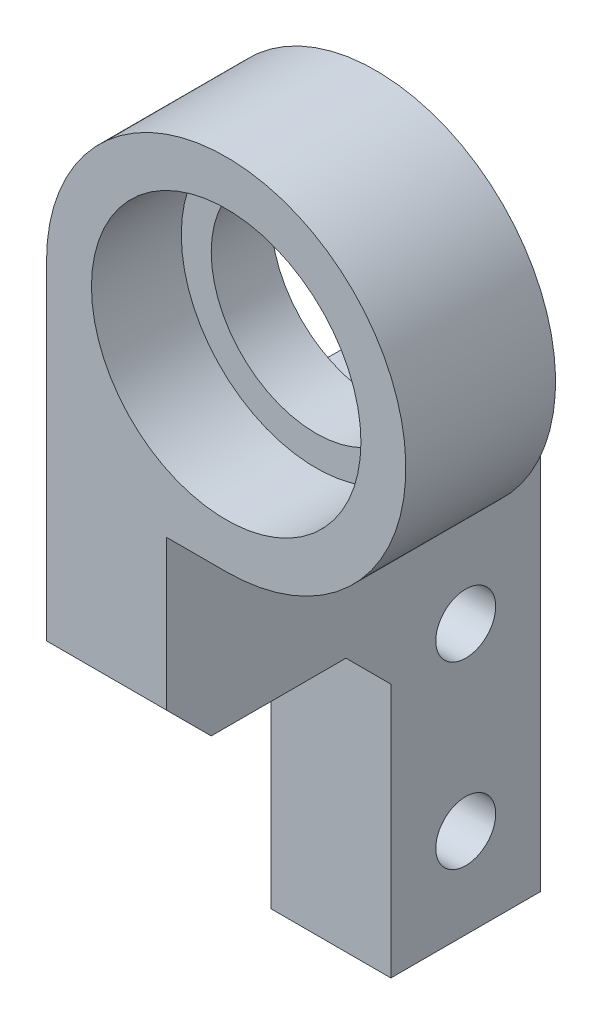
SolidWorks part; units mm, degrees
material "1060 合金"
ref_plane "前视基准面" through (0, 0, 0) normal (0, 0, 1) x (1, 0, 0)
ref_plane "上视基准面" through (0, 0, 0) normal (0, 1, 0) x (1, 0, 0)
ref_plane "右视基准面" through (0, 0, 0) normal (1, 0, 0) x (0, 0, -1)
sketch "草图1" plane through (0, 0, 0) normal (0, 0, 1) x (1, 0, 0)
  line L0 (0, 0) -> (8, 0)
  line L1 (8, 0) -> (8, 33)
  line L2 (0, 0) -> (0, 45)
  line L3 (12, 33) -> (8, 33)
  arc A0 (12, 33) -> (0, 45) centre (12, 45) ccw
  circle A1 centre (12, 45) radius 7
  dimension "D2" = 24
  dimension "D4" = 14
  dimension "D1" = 8
  dimension "D3" = 45
extrude "凸台-拉伸1" add sketch "草图1" along normal mid plane 25
sketch "草图5" plane through (0, 0, 0) normal (1, 0, 0) x (0, 0, -1)
  line L0 (-12.5, 57) -> (-12.5, 33) construction
  line L1 (-12.5, 57) -> (-2.5, 57)
  line L2 (-12.5, 57) -> (-12.5, 20)
  line L4 (-2.5, 57) -> (-2.5, 30)
  line L5 (12.5, 0) -> (12.5, 33) construction
  line L6 (12.5, 0) -> (2.5, 0)
  line L7 (12.5, 0) -> (12.5, 30)
  line L9 (2.5, 0) -> (2.5, 20)
  line L10 (2.5, 20) -> (-12.5, 20)
  line L11 (-12.5, 0) -> (-12.5, 33) construction
  line L14 (12.5, 30) -> (-2.5, 30)
  line L15 (-12.5, 0) -> (12.5, 0) construction
  line L16 (12.5, 57) -> (-12.5, 57) construction
  dimension "D1" = 10
  dimension "D2" = 10
  dimension "D3" = 10
  dimension "D4" = 30
extrude "切除-拉伸3" cut sketch "草图5" against normal through all and the other way through all flip side to cut
sketch "草图2" plane through (0, 0, 0) normal (-1, 0, 0) x (0, 0, 1)
  line L0 (-2.5, 0) -> (-12.5, 0) construction
  line L1 (-2.5, 0) -> (-12.5, 0) construction
  circle A0 centre (-7.5, 18) radius 2
  circle A1 centre (-7.5, 6) radius 2
  point P11 (-7.5, 0)
  dimension "D1" = 4
  dimension "D2" = 12
  dimension "D3" = 6
extrude "切除-拉伸1" cut sketch "草图2" against normal through all
sketch "草图4" plane through (0, 0, 12.5) normal (0, 0, 1) x (1, 0, 0)
  circle A0 centre (12, 45) radius 9
  dimension "D1" = 18
extrude "切除-拉伸2" cut sketch "草图4" against normal blind 6
chamfer "倒角1" distance 3 angle 45 4 edges at (4, 30, 2.5) (4, 30, -12.5) (4, 20, -2.5) (4, 20, 12.5)
